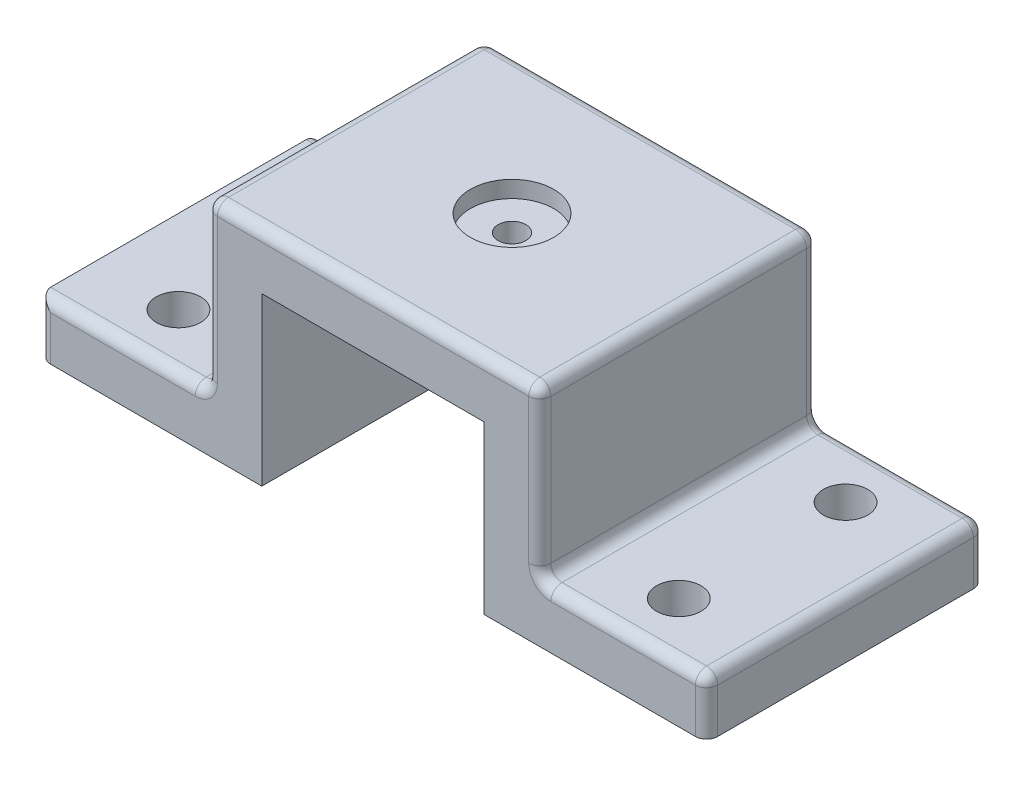
SolidWorks part; units mm, degrees
material "Cast Alloy Steel"
ref_plane "Front Plane" through (0, 0, 0) normal (0, 0, 1) x (1, 0, 0)
ref_plane "Top Plane" through (0, 0, 0) normal (0, 1, 0) x (1, 0, 0)
ref_plane "Right Plane" through (0, 0, 0) normal (1, 0, 0) x (0, 0, -1)
sketch "Sketch1" plane through (0, 0, 0) normal (0, 0, 1) x (1, 0, 0)
  line L0 (-76.2, 0) -> (-25.4, 0)
  line L1 (-25.4, 0) -> (-25.4, 38.1)
  line L2 (-25.4, 38.1) -> (25.4, 38.1)
  line L3 (25.4, 38.1) -> (25.4, 0)
  line L4 (25.4, 0) -> (76.2, 0)
  point P5 (0, 38.1)
  dimension "D1" = 50.8
  dimension "D2" = 38.1
extrude "Extrude-Thin1" add sketch "Sketch1" along normal mid plane 63.5 thin thin type one direction reverse wall 12.7
hole_wizard "CBORE for #00 Binding Head Machine Screw2" positions "Sketch5" profile "Sketch6" counterbore size "#00" standard "ANSI Inch" end condition through all
sketch "Sketch5" plane through (0, 50.8, 0) normal (0, 1, 0) x (1, 0, 0)
  point P0 (0, 0)
sketch "Sketch6" plane through (0, 50.8, 0) normal (1, 0, 0) x (0, 0, 1)
  line L0 (0, 0) -> (0, 50.8)
  line L1 (0, 50.8) -> (3.175, 50.8)
  line L3 (3.175, 50.8) -> (3.175, 3.81)
  line L4 (3.175, 3.81) -> (9.525, 3.81)
  line L5 (9.525, 3.81) -> (9.525, 0)
  line L7 (9.525, 0) -> (0, 0)
  line L11 (0, -6.35) -> (0, 107.95) construction
  dimension "Thru Hole Dia." = 6.35
  dimension "Thru Hole Depth" = 50.8
  dimension "C'Bore Dia." = 19.05
  dimension "C'Bore Depth" = 3.81
sketch "Sketch7" plane through (0, 12.7, 0) normal (0, 1, 0) x (1, 0, 0)
  line L0 (-76.2, -31.75) -> (-76.2, 31.75) construction
  line L1 (-76.2, -31.75) -> (-38.1, -31.75) construction
  circle A0 centre (-57.15, -19.05) radius 5.08
  dimension "D1" = 10.16
  dimension "D2" = 19.05
  dimension "D3" = 12.7
extrude "Cut-Extrude1" cut sketch "Sketch7" against normal through all
pattern_linear "LPattern1" count 2 spacing 38.1 along (0, 0, -1) count 2 spacing 114.3 along (1, 0, 0) of "Cut-Extrude1"
fillet "Fillet1" radius 2.54 19 edges at (-57.15, 12.7, 31.75) (-57.15, 12.7, -31.75) (57.15, 12.7, 31.75) (57.15, 12.7, -31.75) (-38.1, 50.8, 0) (-38.1, 31.75, 31.75) (-38.1, 12.7, 0) (-38.1, 31.75, -31.75) (38.1, 12.7, 0) (38.1, 31.75, 31.75) (38.1, 50.8, 0) (38.1, 31.75, -31.75) (-76.2, 6.35, 31.75) (-76.2, 6.35, -31.75) (76.2, 6.35, -31.75) (76.2, 6.35, 31.75) (76.2, 12.7, 0) (0, 50.8, -31.75) (0, 50.8, 31.75)
